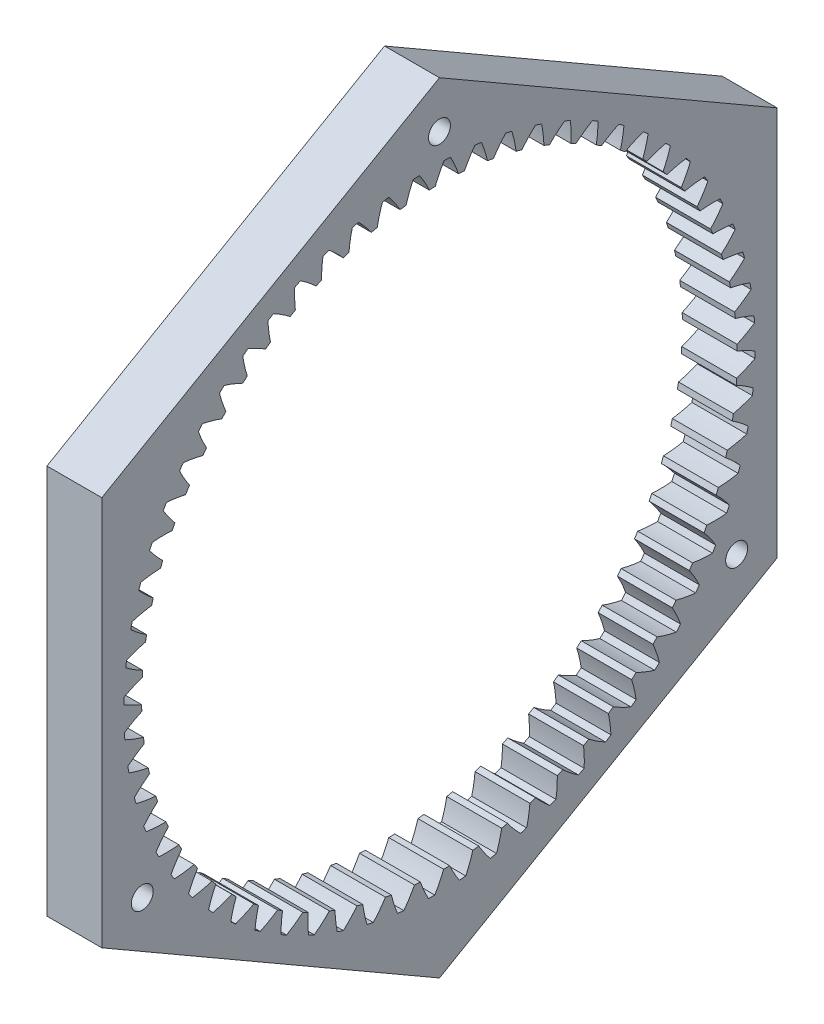
SolidWorks part; units mm, degrees
ref_plane "Front Plane" through (0, 0, 0) normal (0, 0, 1) x (1, 0, 0)
ref_plane "Top Plane" through (0, 0, 0) normal (0, 1, 0) x (1, 0, 0)
ref_plane "Right Plane" through (0, 0, 0) normal (1, 0, 0) x (0, 0, -1)
ref_plane "Plane1" through (-234.2172, 0, 0) normal (1, 0, 0) x (0, 0, -1)
sketch "Sketch1" plane through (-234.2172, 0, 0) normal (1, 0, 0) x (0, 0, -1)
  circle A0 centre (8.1215, -4.7146) radius 61.49
  arc A1 (-39.3484, -30.957) -> (-42.9824, -31.0708) centre (-41.8876, -7.9467) cw
  arc A2 (-42.9824, -31.0708) -> (-43.5088, -30.024) centre (8.1215, -4.7146) cw
  arc A3 (-43.5088, -30.024) -> (-41.2506, -27.1746) centre (-24.2925, -42.9336) cw
  arc A4 (-41.2506, -27.1746) -> (-41.692, -26.1778) centre (8.1215, -4.7146) cw
  arc A5 (-41.692, -26.1778) -> (-45.3196, -25.9348) centre (-41.9636, -3.0294) cw
  arc A6 (-45.3196, -25.9348) -> (-45.7409, -24.8415) centre (8.1215, -4.7146) cw
  arc A7 (-45.7409, -24.8415) -> (-43.2143, -22.2271) centre (-27.8826, -39.5725) cw
  arc A8 (-43.2143, -22.2271) -> (-43.5559, -21.1918) centre (8.1215, -4.7146) cw
  arc A9 (-43.5559, -21.1918) -> (-47.1422, -20.5945) centre (-41.5573, 1.8717) cw
  arc A10 (-47.1422, -20.5945) -> (-47.4543, -19.4651) centre (8.1215, -4.7146) cw
  arc A11 (-47.4543, -19.4651) -> (-44.6836, -17.111) centre (-31.1259, -35.8756) cw
  arc A12 (-44.6836, -17.111) -> (-44.9221, -16.0472) centre (8.1215, -4.7146) cw
  arc A13 (-44.9221, -16.0472) -> (-48.4326, -15.1012) centre (-40.6725, 6.7094) cw
  arc A14 (-48.4326, -15.1012) -> (-48.6325, -13.9467) centre (8.1215, -4.7146) cw
  arc A15 (-48.6325, -13.9467) -> (-45.6444, -11.8755) centre (-33.9912, -31.8786) cw
  arc A16 (-45.6444, -11.8755) -> (-45.7775, -10.7935) centre (8.1215, -4.7146) cw
  arc A17 (-45.7775, -10.7935) -> (-49.1784, -9.5079) centre (-39.3178, 11.437) cw
  arc A18 (-49.1784, -9.5079) -> (-49.2641, -8.3394) centre (8.1215, -4.7146) cw
  arc A19 (-49.2641, -8.3394) -> (-46.0874, -6.571) centre (-36.4509, -27.6201) cw
  arc A20 (-46.0874, -6.571) -> (-46.1137, -5.4812) centre (8.1215, -4.7146) cw
  arc A21 (-46.1137, -5.4812) -> (-49.3723, -3.8685) centre (-37.5062, 16.0091) cw
  arc A22 (-49.3723, -3.8685) -> (-49.3431, -2.6972) centre (8.1215, -4.7146) cw
  arc A23 (-49.3431, -2.6972) -> (-46.0083, -1.2487) centre (-38.4814, -23.1409) cw
  arc A24 (-46.0083, -1.2487) -> (-45.9277, -0.1615) centre (8.1215, -4.7146) cw
  arc A25 (-45.9277, -0.1615) -> (-49.0125, 1.7628) centre (-35.2552, 20.3816) cw
  arc A26 (-49.0125, 1.7628) -> (-48.8686, 2.9256) centre (8.1215, -4.7146) cw
  arc A27 (-48.8686, 2.9256) -> (-45.4079, 4.0403) centre (-40.0631, -18.4843) cw
  arc A28 (-45.4079, 4.0403) -> (-45.2212, 5.1143) centre (8.1215, -4.7146) cw
  arc A29 (-45.2212, 5.1143) -> (-48.1025, 7.3317) centre (-32.5865, 24.5124) cw
  arc A30 (-48.1025, 7.3317) -> (-47.8453, 8.4749) centre (8.1215, -4.7146) cw
  arc A31 (-47.8453, 8.4749) -> (-44.2921, 9.2449) centre (-41.1807, -13.6951) cw
  arc A32 (-44.2921, 9.2449) -> (-44.0009, 10.2955) centre (8.1215, -4.7146) cw
  arc A33 (-44.0009, 10.2955) -> (-46.651, 12.7846) centre (-29.5257, 28.3618) cw
  arc A34 (-46.651, 12.7846) -> (-46.2831, 13.8971) centre (8.1215, -4.7146) cw
  arc A35 (-46.2831, 13.8971) -> (-42.6714, 14.3151) centre (-41.8236, -8.8194) cw
  arc A36 (-42.6714, 14.3151) -> (-42.2787, 15.3321) centre (8.1215, -4.7146) cw
  arc A37 (-42.2787, 15.3321) -> (-44.672, 18.069) centre (-26.1024, 31.8926) cw
  arc A38 (-44.672, 18.069) -> (-44.1968, 19.14) centre (8.1215, -4.7146) cw
  arc A39 (-44.1968, 19.14) -> (-40.5616, 19.2021) centre (-41.9854, -3.9041) cw
  arc A40 (-40.5616, 19.2021) -> (-40.0711, 20.1756) centre (8.1215, -4.7146) cw
  arc A41 (-40.0711, 20.1756) -> (-42.1846, 23.134) centre (-22.3494, 35.0708) cw
  arc A42 (-42.1846, 23.134) -> (-41.6067, 24.1532) centre (8.1215, -4.7146) cw
  arc A43 (-41.6067, 24.1532) -> (-38.125, 23.6281) centre (-43.3088, 1.0659) cw
  arc A44 (-38.125, 23.6281) -> (-37.3993, 24.7795) centre (8.1215, -4.7146) cw
  arc A45 (-37.3993, 24.7795) -> (-39.2127, 27.9307) centre (-18.3031, 37.8659) cw
  arc A46 (-39.2127, 27.9307) -> (-38.5377, 28.8885) centre (8.1215, -4.7146) cw
  arc A47 (-38.5377, 28.8885) -> (-34.9602, 28.2401) centre (-40.8645, 5.8557) cw
  arc A48 (-34.9602, 28.2401) -> (-34.2892, 29.0993) centre (8.1215, -4.7146) cw
  arc A49 (-34.2892, 29.0993) -> (-35.785, 32.4131) centre (-14.0022, 40.2509) cw
  arc A50 (-35.785, 32.4131) -> (-35.0194, 33.3) centre (8.1215, -4.7146) cw
  arc A51 (-35.0194, 33.3) -> (-31.5227, 32.3042) centre (-39.5926, 10.6062) cw
  arc A52 (-31.5227, 32.3042) -> (-30.7707, 33.0934) centre (8.1215, -4.7146) cw
  arc A53 (-30.7707, 33.0934) -> (-31.9344, 36.5379) centre (-9.4883, 42.2029) cw
  arc A54 (-31.9344, 36.5379) -> (-31.0855, 37.3455) centre (8.1215, -4.7146) cw
  arc A55 (-31.0855, 37.3455) -> (-27.7033, 36.0117) centre (-37.8611, 15.2093) cw
  arc A56 (-27.7033, 36.0117) -> (-26.8775, 36.7235) centre (8.1215, -4.7146) cw
  arc A57 (-26.8775, 36.7235) -> (-27.6981, 40.2654) centre (-4.8048, 43.703) cw
  arc A58 (-27.6981, 40.2654) -> (-26.7741, 40.986) centre (8.1215, -4.7146) cw
  arc A59 (-26.7741, 40.986) -> (-23.5389, 39.327) centre (-35.6868, 19.6204) cw
  arc A60 (-23.5389, 39.327) -> (-22.6474, 39.9544) centre (8.1215, -4.7146) cw
  arc A61 (-22.6474, 39.9544) -> (-23.1168, 43.5598) centre (0.0033, 44.7369) cw
  arc A62 (-23.1168, 43.5598) -> (-22.1267, 44.1863) centre (8.1215, -4.7146) cw
  arc A63 (-22.1267, 44.1863) -> (-19.0696, 42.2182) centre (-33.0906, 23.7972) cw
  arc A64 (-19.0696, 42.2182) -> (-18.1209, 42.7552) centre (8.1215, -4.7146) cw
  arc A65 (-18.1209, 42.7552) -> (-18.2347, 46.3892) centre (4.8894, 45.2945) cw
  arc A66 (-18.2347, 46.3892) -> (-17.1879, 46.9156) centre (8.1215, -4.7146) cw
  arc A67 (-17.1879, 46.9156) -> (-14.3384, 44.6574) centre (-30.0975, 27.6994) cw
  arc A68 (-14.3384, 44.6574) -> (-13.3416, 45.0988) centre (8.1215, -4.7146) cw
  arc A69 (-13.3416, 45.0988) -> (-13.0987, 48.7265) centre (9.8068, 45.3705) cw
  arc A70 (-13.0987, 48.7265) -> (-12.0054, 49.1478) centre (8.1215, -4.7146) cw
  arc A71 (-12.0054, 49.1478) -> (-9.391, 46.6211) centre (-26.7363, 31.2894) cw
  arc A72 (-9.391, 46.6211) -> (-8.3557, 46.9627) centre (8.1215, -4.7146) cw
  arc A73 (-8.3557, 46.9627) -> (-7.7584, 50.5491) centre (14.7078, 44.9641) cw
  arc A74 (-7.7584, 50.5491) -> (-6.629, 50.8612) centre (8.1215, -4.7146) cw
  arc A75 (-6.629, 50.8612) -> (-4.2749, 48.0905) centre (-23.0395, 34.5327) cw
  arc A76 (-4.2749, 48.0905) -> (-3.2111, 48.3289) centre (8.1215, -4.7146) cw
  arc A77 (-3.2111, 48.3289) -> (-2.2651, 51.8395) centre (19.5455, 44.0793) cw
  arc A78 (-2.2651, 51.8395) -> (-1.1106, 52.0394) centre (8.1215, -4.7146) cw
  arc A79 (-1.1106, 52.0394) -> (0.9606, 49.0513) centre (-19.0425, 37.398) cw
  arc A80 (0.9606, 49.0513) -> (2.0426, 49.1843) centre (8.1215, -4.7146) cw
  arc A81 (2.0426, 49.1843) -> (3.3282, 52.5852) centre (24.2731, 42.7246) cw
  arc A82 (3.3282, 52.5852) -> (4.4967, 52.671) centre (8.1215, -4.7146) cw
  arc A83 (4.4967, 52.671) -> (6.2651, 49.4942) centre (-14.7839, 39.8578) cw
  arc A84 (6.2651, 49.4942) -> (7.3549, 49.5206) centre (8.1215, -4.7146) cw
  arc A85 (7.3549, 49.5206) -> (8.9676, 52.7791) centre (28.8452, 40.9131) cw
  arc A86 (8.9676, 52.7791) -> (10.139, 52.75) centre (8.1215, -4.7146) cw
  arc A87 (10.139, 52.75) -> (11.5874, 49.4152) centre (-10.3048, 41.8883) cw
  arc A88 (11.5874, 49.4152) -> (12.6746, 49.3346) centre (8.1215, -4.7146) cw
  arc A89 (12.6746, 49.3346) -> (14.5989, 52.4194) centre (33.2177, 38.6621) cw
  arc A90 (14.5989, 52.4194) -> (15.7618, 52.2755) centre (8.1215, -4.7146) cw
  arc A91 (15.7618, 52.2755) -> (16.8764, 48.8148) centre (-5.6482, 43.47) cw
  arc A92 (16.8764, 48.8148) -> (17.9504, 48.628) centre (8.1215, -4.7146) cw
  arc A93 (17.9504, 48.628) -> (20.1679, 51.5093) centre (37.3485, 35.9933) cw
  arc A94 (20.1679, 51.5093) -> (21.311, 51.2522) centre (8.1215, -4.7146) cw
  arc A95 (21.311, 51.2522) -> (22.081, 47.6989) centre (-0.8589, 44.5876) cw
  arc A96 (22.081, 47.6989) -> (23.1316, 47.4078) centre (8.1215, -4.7146) cw
  arc A97 (23.1316, 47.4078) -> (25.6208, 50.0579) centre (41.1979, 32.9326) cw
  arc A98 (25.6208, 50.0579) -> (26.7332, 49.6899) centre (8.1215, -4.7146) cw
  arc A99 (26.7332, 49.6899) -> (27.1512, 46.0783) centre (4.0168, 45.2304) cw
  arc A100 (27.1512, 46.0783) -> (28.1682, 45.6855) centre (8.1215, -4.7146) cw
  arc A101 (28.1682, 45.6855) -> (30.9051, 48.0789) centre (44.7287, 29.5092) cw
  arc A102 (30.9051, 48.0789) -> (31.9761, 47.6037) centre (8.1215, -4.7146) cw
  arc A103 (31.9761, 47.6037) -> (32.0382, 43.9684) centre (8.932, 45.3923) cw
  arc A104 (32.0382, 43.9684) -> (33.0118, 43.4779) centre (8.1215, -4.7146) cw
  arc A105 (33.0118, 43.4779) -> (35.9701, 45.5915) centre (47.9069, 25.7563) cw
  arc A106 (35.9701, 45.5915) -> (36.9894, 45.0136) centre (8.1215, -4.7146) cw
  arc A107 (36.9894, 45.0136) -> (36.6948, 41.3898) centre (13.8394, 45.0716) cw
  arc A108 (36.6948, 41.3898) -> (37.6156, 40.8062) centre (8.1215, -4.7146) cw
  arc A109 (37.6156, 40.8062) -> (40.7669, 42.6196) centre (50.702, 21.7099) cw
  arc A110 (40.7669, 42.6196) -> (41.7246, 41.9446) centre (8.1215, -4.7146) cw
  arc A111 (41.7246, 41.9446) -> (41.0762, 38.3671) centre (18.6918, 44.2714) cw
  arc A112 (41.0762, 38.3671) -> (41.9354, 37.6961) centre (8.1215, -4.7146) cw
  arc A113 (41.9354, 37.6961) -> (45.2492, 39.1919) centre (53.0871, 17.4091) cw
  arc A114 (45.2492, 39.1919) -> (46.1362, 38.4262) centre (8.1215, -4.7146) cw
  arc A115 (46.1362, 38.4262) -> (45.1403, 34.9295) centre (23.4424, 42.9994) cw
  arc A116 (45.1403, 34.9295) -> (45.9296, 34.1775) centre (8.1215, -4.7146) cw
  arc A117 (45.9296, 34.1775) -> (49.374, 35.3413) centre (55.039, 12.8951) cw
  arc A118 (49.374, 35.3413) -> (50.1817, 34.4924) centre (8.1215, -4.7146) cw
  arc A119 (50.1817, 34.4924) -> (48.8478, 31.1101) centre (28.0454, 41.2679) cw
  arc A120 (48.8478, 31.1101) -> (49.5596, 30.2844) centre (8.1215, -4.7146) cw
  arc A121 (49.5596, 30.2844) -> (53.1016, 31.105) centre (56.5392, 8.2116) cw
  arc A122 (53.1016, 31.105) -> (53.8221, 30.181) centre (8.1215, -4.7146) cw
  arc A123 (53.8221, 30.181) -> (52.1632, 26.9458) centre (32.4565, 39.0936) cw
  arc A124 (52.1632, 26.9458) -> (52.7906, 26.0542) centre (8.1215, -4.7146) cw
  arc A125 (52.7906, 26.0542) -> (56.3959, 26.5237) centre (57.573, 3.4036) cw
  arc A126 (56.3959, 26.5237) -> (57.0224, 25.5335) centre (8.1215, -4.7146) cw
  arc A127 (57.0224, 25.5335) -> (55.0544, 22.4765) centre (36.6333, 36.4974) cw
  arc A128 (55.0544, 22.4765) -> (55.5913, 21.5277) centre (8.1215, -4.7146) cw
  arc A129 (55.5913, 21.5277) -> (59.2253, 21.6415) centre (58.1306, -1.4826) cw
  arc A130 (59.2253, 21.6415) -> (59.7518, 20.5947) centre (8.1215, -4.7146) cw
  arc A131 (59.7518, 20.5947) -> (57.4936, 17.7453) centre (40.5355, 33.5044) cw
  arc A132 (57.4936, 17.7453) -> (57.935, 16.7485) centre (8.1215, -4.7146) cw
  arc A133 (57.935, 16.7485) -> (61.5626, 16.5056) centre (58.2066, -6.3999) cw
  arc A134 (61.5626, 16.5056) -> (61.9839, 15.4122) centre (8.1215, -4.7146) cw
  arc A135 (61.9839, 15.4122) -> (59.4573, 12.7978) centre (44.1255, 30.1432) cw
  arc A136 (59.4573, 12.7978) -> (59.7989, 11.7626) centre (8.1215, -4.7146) cw
  arc A137 (59.7989, 11.7626) -> (63.3852, 11.1652) centre (57.8003, -11.301) cw
  arc A138 (63.3852, 11.1652) -> (63.6973, 10.0359) centre (8.1215, -4.7146) cw
  arc A139 (63.6973, 10.0359) -> (60.9266, 7.6817) centre (47.3688, 26.4463) cw
  arc A140 (60.9266, 7.6817) -> (61.1651, 6.618) centre (8.1215, -4.7146) cw
  arc A141 (61.1651, 6.618) -> (64.6756, 5.672) centre (56.9155, -16.1386) cw
  arc A142 (64.6756, 5.672) -> (64.8755, 4.5175) centre (8.1215, -4.7146) cw
  arc A143 (64.8755, 4.5175) -> (61.8874, 2.4462) centre (50.2342, 22.4494) cw
  arc A144 (61.8874, 2.4462) -> (62.0204, 1.3642) centre (8.1215, -4.7146) cw
  arc A145 (62.0204, 1.3642) -> (65.4214, 0.0787) centre (55.5608, -20.8663) cw
  arc A146 (65.4214, 0.0787) -> (65.5071, -1.0899) centre (8.1215, -4.7146) cw
  arc A147 (65.5071, -1.0899) -> (62.3304, -2.8582) centre (52.6939, 18.1908) cw
  arc A148 (62.3304, -2.8582) -> (62.3567, -3.9481) centre (8.1215, -4.7146) cw
  arc A149 (62.3567, -3.9481) -> (65.6153, -5.5608) centre (53.7492, -25.4384) cw
  arc A150 (65.6153, -5.5608) -> (65.5861, -6.7321) centre (8.1215, -4.7146) cw
  arc A151 (65.5861, -6.7321) -> (62.2513, -8.1806) centre (54.7244, 13.7116) cw
  arc A152 (62.2513, -8.1806) -> (62.1707, -9.2677) centre (8.1215, -4.7146) cw
  arc A153 (62.1707, -9.2677) -> (65.2555, -11.1921) centre (51.4982, -29.8109) cw
  arc A154 (65.2555, -11.1921) -> (65.1116, -12.3549) centre (8.1215, -4.7146) cw
  arc A155 (65.1116, -12.3549) -> (61.6509, -13.4695) centre (56.3061, 9.055) cw
  arc A156 (61.6509, -13.4695) -> (61.4642, -14.5436) centre (8.1215, -4.7146) cw
  arc A157 (61.4642, -14.5436) -> (64.3455, -16.761) centre (48.8295, -33.9417) cw
  arc A158 (64.3455, -16.761) -> (64.0883, -17.9041) centre (8.1215, -4.7146) cw
  arc A159 (64.0883, -17.9041) -> (60.535, -18.6742) centre (57.4237, 4.2658) cw
  arc A160 (60.535, -18.6742) -> (60.2439, -19.7247) centre (8.1215, -4.7146) cw
  arc A161 (60.2439, -19.7247) -> (62.894, -22.2139) centre (45.7687, -37.791) cw
  arc A162 (62.894, -22.2139) -> (62.526, -23.3263) centre (8.1215, -4.7146) cw
  arc A163 (62.526, -23.3263) -> (58.9144, -23.7444) centre (58.0666, -0.6099) cw
  arc A164 (58.9144, -23.7444) -> (58.5217, -24.7613) centre (8.1215, -4.7146) cw
  arc A165 (58.5217, -24.7613) -> (60.915, -27.4983) centre (42.3454, -41.3218) cw
  arc A166 (60.915, -27.4983) -> (60.4398, -28.5693) centre (8.1215, -4.7146) cw
  arc A167 (60.4398, -28.5693) -> (56.8046, -28.6313) centre (58.2284, -5.5251) cw
  arc A168 (56.8046, -28.6313) -> (56.3141, -29.6049) centre (8.1215, -4.7146) cw
  arc A169 (56.3141, -29.6049) -> (58.4276, -32.5632) centre (38.5924, -44.5001) cw
  arc A170 (58.4276, -32.5632) -> (57.8497, -33.5825) centre (8.1215, -4.7146) cw
  arc A171 (57.8497, -33.5825) -> (54.2259, -33.2879) centre (57.9077, -10.4326) cw
  arc A172 (54.2259, -33.2879) -> (53.6423, -34.2087) centre (8.1215, -4.7146) cw
  arc A173 (53.6423, -34.2087) -> (55.4557, -37.36) centre (34.5461, -47.2952) cw
  arc A174 (55.4557, -37.36) -> (54.7807, -38.3177) centre (8.1215, -4.7146) cw
  arc A175 (54.7807, -38.3177) -> (51.2032, -37.6694) centre (57.1075, -15.2849) cw
  arc A176 (51.2032, -37.6694) -> (50.5322, -38.5285) centre (8.1215, -4.7146) cw
  arc A177 (50.5322, -38.5285) -> (52.028, -41.8424) centre (30.2452, -49.6802) cw
  arc A178 (52.028, -41.8424) -> (51.2624, -42.7293) centre (8.1215, -4.7146) cw
  arc A179 (51.2624, -42.7293) -> (47.7656, -41.7334) centre (55.8355, -20.0355) cw
  arc A180 (47.7656, -41.7334) -> (47.0136, -42.5227) centre (8.1215, -4.7146) cw
  arc A181 (47.0136, -42.5227) -> (48.1774, -45.9672) centre (25.7313, -51.6322) cw
  arc A182 (48.1774, -45.9672) -> (47.3285, -46.7748) centre (8.1215, -4.7146) cw
  arc A183 (47.3285, -46.7748) -> (43.9463, -45.441) centre (54.1041, -24.6385) cw
  arc A184 (43.9463, -45.441) -> (43.1205, -46.1527) centre (8.1215, -4.7146) cw
  arc A185 (43.1205, -46.1527) -> (43.9411, -49.6947) centre (21.0477, -53.1323) cw
  arc A186 (43.9411, -49.6947) -> (43.0171, -50.4152) centre (8.1215, -4.7146) cw
  arc A187 (43.0171, -50.4152) -> (39.7819, -48.7563) centre (51.9298, -29.0497) cw
  arc A188 (39.7819, -48.7563) -> (38.8904, -49.3837) centre (8.1215, -4.7146) cw
  arc A189 (38.8904, -49.3837) -> (39.3598, -52.989) centre (16.2397, -54.1662) cw
  arc A190 (39.3598, -52.989) -> (38.3696, -53.6155) centre (8.1215, -4.7146) cw
  arc A191 (38.3696, -53.6155) -> (35.3126, -51.6475) centre (49.3336, -33.2265) cw
  arc A192 (35.3126, -51.6475) -> (34.3639, -52.1845) centre (8.1215, -4.7146) cw
  arc A193 (34.3639, -52.1845) -> (34.4776, -55.8185) centre (11.3535, -54.7238) cw
  arc A194 (34.4776, -55.8185) -> (33.4309, -56.3449) centre (8.1215, -4.7146) cw
  arc A195 (33.4309, -56.3449) -> (30.5814, -54.0867) centre (46.3405, -37.1287) cw
  arc A196 (30.5814, -54.0867) -> (29.5846, -54.5281) centre (8.1215, -4.7146) cw
  arc A197 (29.5846, -54.5281) -> (29.3417, -58.1558) centre (6.4362, -54.7998) cw
  arc A198 (29.3417, -58.1558) -> (28.2483, -58.577) centre (8.1215, -4.7146) cw
  arc A199 (28.2483, -58.577) -> (25.634, -56.0504) centre (42.9793, -40.7187) cw
  arc A200 (25.634, -56.0504) -> (24.5987, -56.392) centre (8.1215, -4.7146) cw
  arc A201 (24.5987, -56.392) -> (24.0014, -59.9784) centre (1.5351, -54.3934) cw
  arc A202 (24.0014, -59.9784) -> (22.872, -60.2905) centre (8.1215, -4.7146) cw
  arc A203 (22.872, -60.2905) -> (20.5179, -57.5197) centre (39.2824, -43.962) cw
  arc A204 (20.5179, -57.5197) -> (19.4541, -57.7582) centre (8.1215, -4.7146) cw
  arc A205 (19.4541, -57.7582) -> (18.5081, -61.2688) centre (-3.3025, -53.5086) cw
  arc A206 (18.5081, -61.2688) -> (17.3536, -61.4687) centre (8.1215, -4.7146) cw
  arc A207 (17.3536, -61.4687) -> (15.2824, -58.4805) centre (35.2855, -46.8273) cw
  arc A208 (15.2824, -58.4805) -> (14.2004, -58.6136) centre (8.1215, -4.7146) cw
  arc A209 (14.2004, -58.6136) -> (12.9148, -62.0145) centre (-8.0301, -52.1539) cw
  arc A210 (12.9148, -62.0145) -> (11.7463, -62.1003) centre (8.1215, -4.7146) cw
  arc A211 (11.7463, -62.1003) -> (9.9779, -58.9235) centre (31.0269, -49.2871) cw
  arc A212 (9.9779, -58.9235) -> (8.8881, -58.9499) centre (8.1215, -4.7146) cw
  arc A213 (8.8881, -58.9499) -> (7.2754, -62.2084) centre (-12.6022, -50.3423) cw
  arc A214 (7.2754, -62.2084) -> (6.104, -62.1792) centre (8.1215, -4.7146) cw
  arc A215 (6.104, -62.1792) -> (4.6556, -58.8444) centre (26.5478, -51.3176) cw
  arc A216 (4.6556, -58.8444) -> (3.5684, -58.7639) centre (8.1215, -4.7146) cw
  arc A217 (3.5684, -58.7639) -> (1.6441, -61.8486) centre (-16.9747, -48.0913) cw
  arc A218 (1.6441, -61.8486) -> (0.4812, -61.7048) centre (8.1215, -4.7146) cw
  arc A219 (0.4812, -61.7048) -> (-0.6334, -58.2441) centre (21.8912, -52.8992) cw
  arc A220 (-0.6334, -58.2441) -> (-1.7074, -58.0573) centre (8.1215, -4.7146) cw
  arc A221 (-1.7074, -58.0573) -> (-3.9249, -60.9386) centre (-21.1056, -45.4226) cw
  arc A222 (-3.9249, -60.9386) -> (-5.068, -60.6815) centre (8.1215, -4.7146) cw
  arc A223 (-5.068, -60.6815) -> (-5.838, -57.1282) centre (17.1019, -54.0169) cw
  arc A224 (-5.838, -57.1282) -> (-6.8886, -56.837) centre (8.1215, -4.7146) cw
  arc A225 (-6.8886, -56.837) -> (-9.3778, -59.4871) centre (-24.9549, -42.3618) cw
  arc A226 (-9.3778, -59.4871) -> (-10.4902, -59.1192) centre (8.1215, -4.7146) cw
  arc A227 (-10.4902, -59.1192) -> (-10.9082, -55.5075) centre (12.2262, -54.6597) cw
  arc A228 (-10.9082, -55.5075) -> (-11.9252, -55.1148) centre (8.1215, -4.7146) cw
  arc A229 (-11.9252, -55.1148) -> (-14.6621, -57.5082) centre (-28.4857, -38.9385) cw
  arc A230 (-14.6621, -57.5082) -> (-15.7332, -57.0329) centre (8.1215, -4.7146) cw
  arc A231 (-15.7332, -57.0329) -> (-15.7952, -53.3977) centre (7.311, -54.8215) cw
  arc A232 (-15.7952, -53.3977) -> (-16.7688, -52.9072) centre (8.1215, -4.7146) cw
  arc A233 (-16.7688, -52.9072) -> (-19.7271, -55.0207) centre (-31.6639, -35.1856) cw
  arc A234 (-19.7271, -55.0207) -> (-20.7464, -54.4429) centre (8.1215, -4.7146) cw
  arc A235 (-20.7464, -54.4429) -> (-20.4518, -50.819) centre (2.4036, -54.5008) cw
  arc A236 (-20.4518, -50.819) -> (-21.3726, -50.2355) centre (8.1215, -4.7146) cw
  arc A237 (-21.3726, -50.2355) -> (-24.5239, -52.0489) centre (-34.459, -31.1392) cw
  arc A238 (-24.5239, -52.0489) -> (-25.4816, -51.3739) centre (8.1215, -4.7146) cw
  arc A239 (-25.4816, -51.3739) -> (-24.8332, -47.7964) centre (-2.4488, -53.7006) cw
  arc A240 (-24.8332, -47.7964) -> (-25.6924, -47.1253) centre (8.1215, -4.7146) cw
  arc A241 (-25.6924, -47.1253) -> (-29.0062, -48.6211) centre (-36.8441, -26.8383) cw
  arc A242 (-29.0062, -48.6211) -> (-29.8932, -47.8555) centre (8.1215, -4.7146) cw
  arc A243 (-29.8932, -47.8555) -> (-28.8973, -44.3588) centre (-7.1994, -52.4287) cw
  arc A244 (-28.8973, -44.3588) -> (-29.6866, -43.6068) centre (8.1215, -4.7146) cw
  arc A245 (-29.6866, -43.6068) -> (-33.1311, -44.7706) centre (-38.796, -22.3244) cw
  arc A246 (-33.1311, -44.7706) -> (-33.9387, -43.9217) centre (8.1215, -4.7146) cw
  arc A247 (-33.9387, -43.9217) -> (-32.6048, -40.5394) centre (-11.8024, -50.6972) cw
  arc A248 (-32.6048, -40.5394) -> (-33.3166, -39.7137) centre (8.1215, -4.7146) cw
  arc A249 (-33.3166, -39.7137) -> (-36.8586, -40.5342) centre (-40.2962, -17.6409) cw
  arc A250 (-36.8586, -40.5342) -> (-37.5791, -39.6103) centre (8.1215, -4.7146) cw
  arc A251 (-37.5791, -39.6103) -> (-35.9202, -36.375) centre (-16.2135, -48.5229) cw
  arc A252 (-35.9202, -36.375) -> (-36.5476, -35.4835) centre (8.1215, -4.7146) cw
  arc A253 (-36.5476, -35.4835) -> (-40.1529, -35.9529) centre (-41.33, -12.8329) cw
  arc A254 (-40.1529, -35.9529) -> (-40.7794, -34.9628) centre (8.1215, -4.7146) cw
  arc A255 (-40.7794, -34.9628) -> (-38.8114, -31.9057) centre (-20.3903, -45.9267) cw
  arc A256 (-38.8114, -31.9057) -> (-39.3484, -30.957) centre (8.1215, -4.7146) cw
  dimension "D1" = 122.98
  dimension "D2" = 57.5
extrude "Boss-Extrude1" add sketch "Sketch1" against normal blind 10
sketch "Sketch2" plane through (-234.2172, 0, 0) normal (1, 0, 0) x (0, 0, -1)
  line L1 (8.1215, 66.2879) -> (-53.3685, 30.7866)
  line L2 (-53.3685, 30.7866) -> (-53.3685, -40.2159)
  line L3 (-53.3685, -40.2159) -> (8.1215, -75.7172)
  line L4 (8.1215, -75.7172) -> (69.6115, -40.2159)
  line L5 (69.6115, -40.2159) -> (69.6115, 30.7866)
  line L6 (69.6115, 30.7866) -> (8.1215, 66.2879)
  circle A0 centre (8.1215, -4.7146) radius 61.49 construction
  circle A1 centre (8.1215, -4.7146) radius 61.49 construction
  circle A2 centre (8.1215, -4.7146) radius 61.49
  point P0 (8.1215, 56.7754)
extrude "Boss-Extrude2" add sketch "Sketch2" against normal up to surface (10 mm away) contours A2 L5 L6 | A2 L6 L1 | A2 L1 L2 | A2 L2 L3 | A2 L3 L4 | A2 L4 L5 up to face at (-244.2172, -4.7155, -8.121)
sketch "Sketch3" plane through (-234.2172, 0, 0) normal (1, 0, 0) x (0, 0, -1)
  circle A0 centre (8.1215, -4.7146) radius 62.5 construction
  arc A1 (65.5861, -6.7321) -> (65.6153, -5.5608) centre (8.1215, -4.7146) ccw construction
  circle A2 centre (8.1215, 57.7854) radius 2
  circle A3 centre (62.2481, -35.9646) radius 2
  circle A4 centre (-46.0051, -35.9646) radius 2
  point P5 (8.1215, 57.7854)
  point P15 (8.1215, -4.7146)
  dimension "D1" = 125
  dimension "D2" = 4
  dimension "D3" = 3
extrude "Cut-Extrude1" cut sketch "Sketch3" against normal through all
